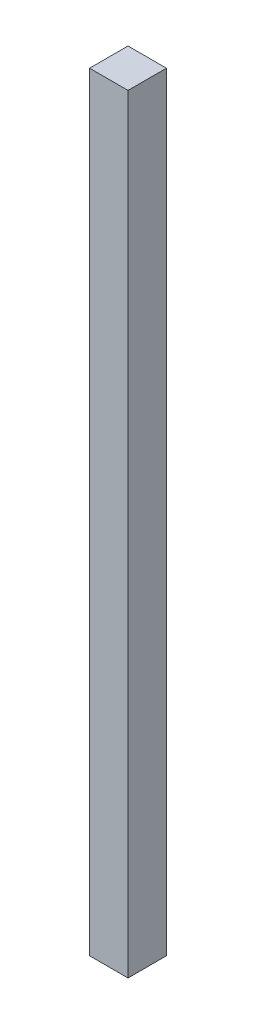
SolidWorks part; units mm, degrees
ref_plane "Front Plane" through (0, 0, 0) normal (0, 0, 1) x (1, 0, 0)
ref_plane "Top Plane" through (0, 0, 0) normal (0, 1, 0) x (1, 0, 0)
ref_plane "Right Plane" through (0, 0, 0) normal (1, 0, 0) x (0, 0, -1)
sketch "Sketch1" plane through (0, 0, 0) normal (0, 1, 0) x (1, 0, 0)
  line L1 (0.625, -0.625) -> (-0.625, -0.625)
  line L2 (0.625, -0.625) -> (0.625, 0.625)
  line L3 (0.625, 0.625) -> (-0.625, 0.625)
  line L4 (-0.625, -0.625) -> (-0.625, 0.625)
  circle A0 centre (0, 0) radius 0.625 construction
  point P0 (0, 0)
  point P7 (0, 0.625)
  point P9 (-0.625, 0)
  dimension "D1" = 1.25
  dimension "D2" = 1.25
extrude "Boss-Extrude1" add sketch "Sketch1" along normal blind 25
